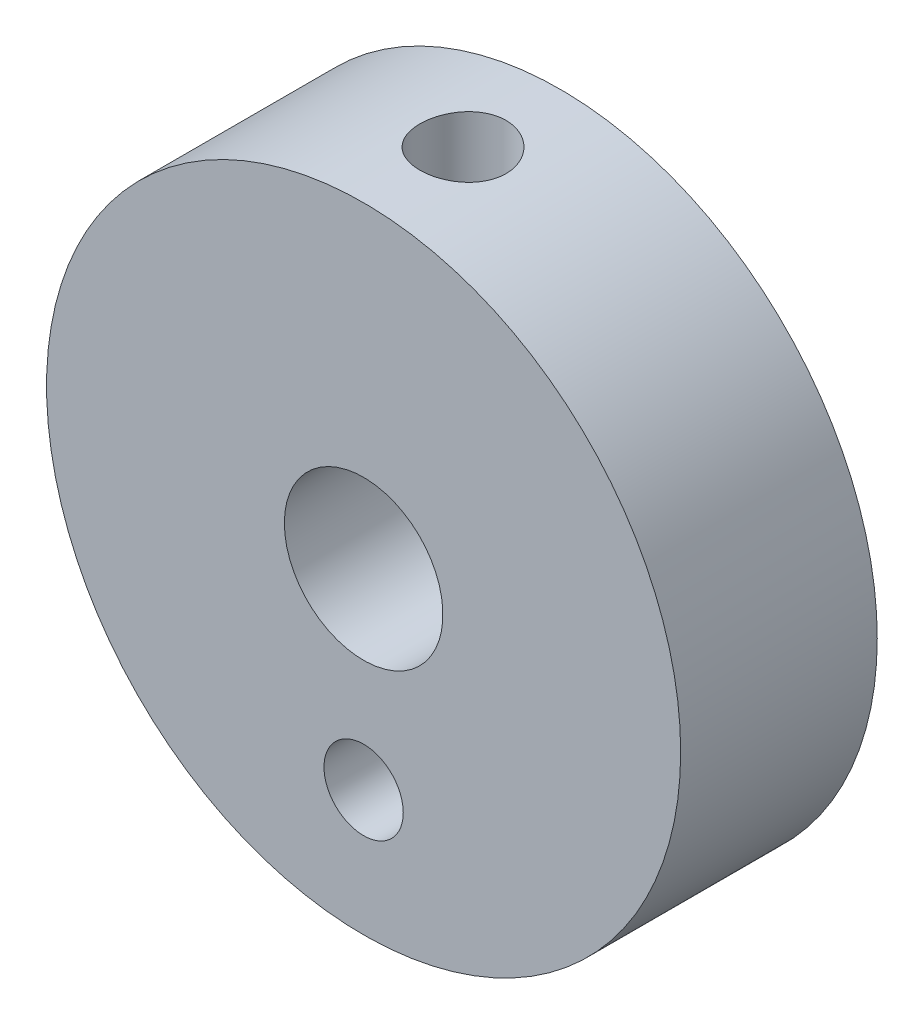
SolidWorks part; units mm, degrees
ref_plane "Front Plane" through (0, 0, 0) normal (0, 0, 1) x (1, 0, 0)
ref_plane "Top Plane" through (0, 0, 0) normal (0, 1, 0) x (1, 0, 0)
ref_plane "Right Plane" through (0, 0, 0) normal (1, 0, 0) x (0, 0, -1)
sketch "Sketch1" plane through (0, 0, 0) normal (0, 0, 1) x (1, 0, 0)
  circle A0 centre (0, 0) radius 12.7
  dimension "D1" = 25.4
extrude "Boss-Extrude1" add sketch "Sketch1" along normal blind 7.874
hole_wizard "1/4 (0.2500) Dowel Hole1" positions "Sketch2" profile "Sketch3" hole size "1/4" standard "ANSI Inch" end condition through all
sketch "Sketch2" plane through (0, 0, 0) normal (0, 0, 1) x (1, 0, 0)
  point P0 (0, 0)
sketch "Sketch3" plane through (0, 0, 0) normal (1, 0, 0) x (0, 1, 0)
  line L0 (0, 0) -> (0, 7.874)
  line L1 (0, 7.874) -> (3.175, 7.874)
  line L2 (3.175, 7.874) -> (3.175, 0)
  line L5 (3.175, 0) -> (0, 0)
  line L11 (0, -6.35) -> (0, 107.95) construction
  dimension "Thru Hole Dia." = 6.35
  dimension "Thru Hole Depth" = 7.874
hole_wizard "1/8 (0.1250) Dowel Hole1" positions "Sketch4" profile "Sketch5" hole size "1/8" standard "ANSI Inch" end condition through all
sketch "Sketch4" plane through (0, 0, 7.874) normal (0, 0, 1) x (1, 0, 0)
  point P0 (0, -7.6697)
sketch "Sketch5" plane through (0, -7.6697, 7.874) normal (1, 0, 0) x (0, -1, 0)
  line L0 (0, 0) -> (0, 7.874)
  line L1 (0, 7.874) -> (1.5875, 7.874)
  line L2 (1.5875, 7.874) -> (1.5875, 0)
  line L5 (1.5875, 0) -> (0, 0)
  line L11 (0, -6.35) -> (0, 107.95) construction
  dimension "Thru Hole Dia." = 3.175
  dimension "Thru Hole Depth" = 7.874
hole_wizard "#8-32 Tapped Hole1" positions "Sketch6" profile "Sketch7" tap size "#8-32" standard "ANSI Inch"
sketch "Sketch6" plane through (0, 0, 0) normal (0, 1, 0) x (1, 0, 0)
  point P0 (0, -3.8929)
sketch "Sketch7" plane through (0, 0, 3.8929) normal (1, 0, 0) x (0, 0, -1)
  line L0 (0, 0) -> (0, 13.97)
  line L1 (0, 13.97) -> (1.7272, 12.9322)
  line L2 (1.7272, 12.9322) -> (1.7272, 0)
  line L5 (1.7272, 0) -> (0, 0)
  line L10 (0, 13.97) -> (-1.7272, 12.9322) construction
  line L11 (0, -6.35) -> (0, 107.95) construction
  dimension "Tap Drill Dia." = 3.4544
  dimension "Tap Drill Depth" = 13.97
  dimension "Drill Angle" = 118
cosmetic thread "Hole Thread1" parameters "D1"=8.382, "D2"=4.1656
